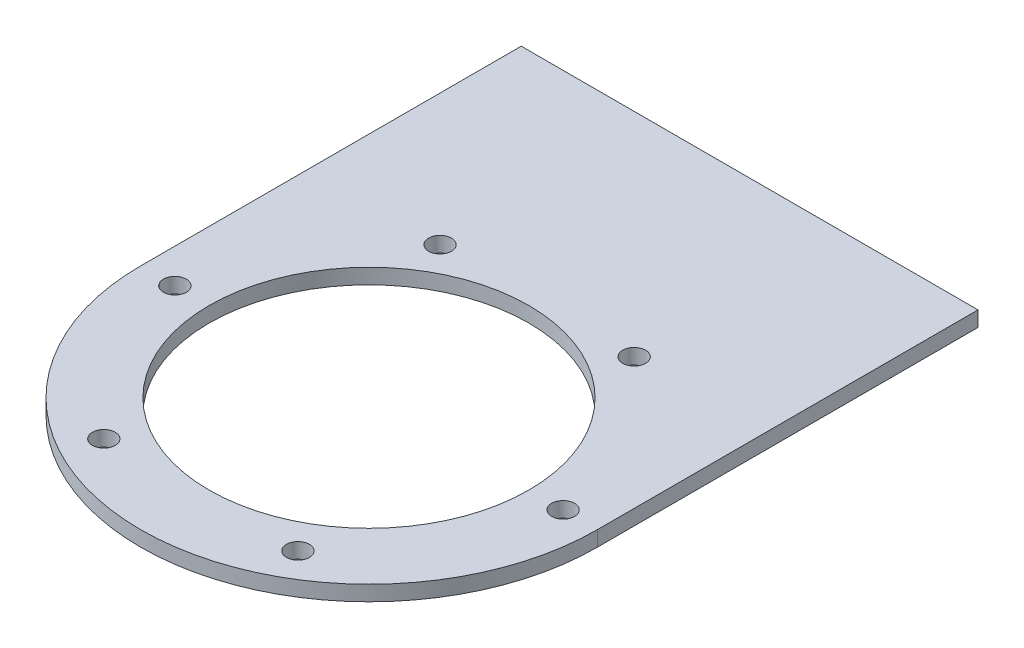
SolidWorks part; units mm, degrees
ref_plane "Front Plane" through (0, 0, 0) normal (0, 0, 1) x (1, 0, 0)
ref_plane "Top Plane" through (0, 0, 0) normal (0, 1, 0) x (1, 0, 0)
ref_plane "Right Plane" through (0, 0, 0) normal (1, 0, 0) x (0, 0, -1)
sketch "Sketch1" plane through (0, 0, 0) normal (0, 1, 0) x (1, 0, 0)
  line L0 (0, 0) -> (43.7646, 0) construction
  line L1 (43.7646, 0) -> (-48.6292, 0) construction
  line L2 (-48.6292, 0) -> (0, 0) construction
  line L3 (0, 0) -> (22.035, -38.1657) construction
  line L4 (22.035, -38.1657) -> (-21.6364, 37.4753) construction
  line L5 (0, 0) -> (19.8864, 34.4443) construction
  line L6 (19.8864, 34.4443) -> (-18.557, -32.1416) construction
  line L7 (-30, 0) -> (-30, 50)
  line L8 (-30, 50) -> (30, 50)
  line L9 (30, 50) -> (30, 0)
  circle A1 centre (0, 0) radius 21
  circle A2 centre (0, 0) radius 25.5 construction
  circle A3 centre (-12.75, 22.0836) radius 1.5
  circle A4 centre (12.75, 22.0836) radius 1.5
  circle A5 centre (25.5, 0) radius 1.5
  circle A6 centre (12.75, -22.0836) radius 1.5
  circle A7 centre (-12.75, -22.0836) radius 1.5
  circle A8 centre (-25.5, 0) radius 1.5
  arc A9 (-30, 0) -> (30, 0) centre (0, 0) ccw
  dimension "D1" = 60
  dimension "D3" = 50
  dimension "D2" = 60
extrude "Boss-Extrude1" add sketch "Sketch1" along normal blind 2
